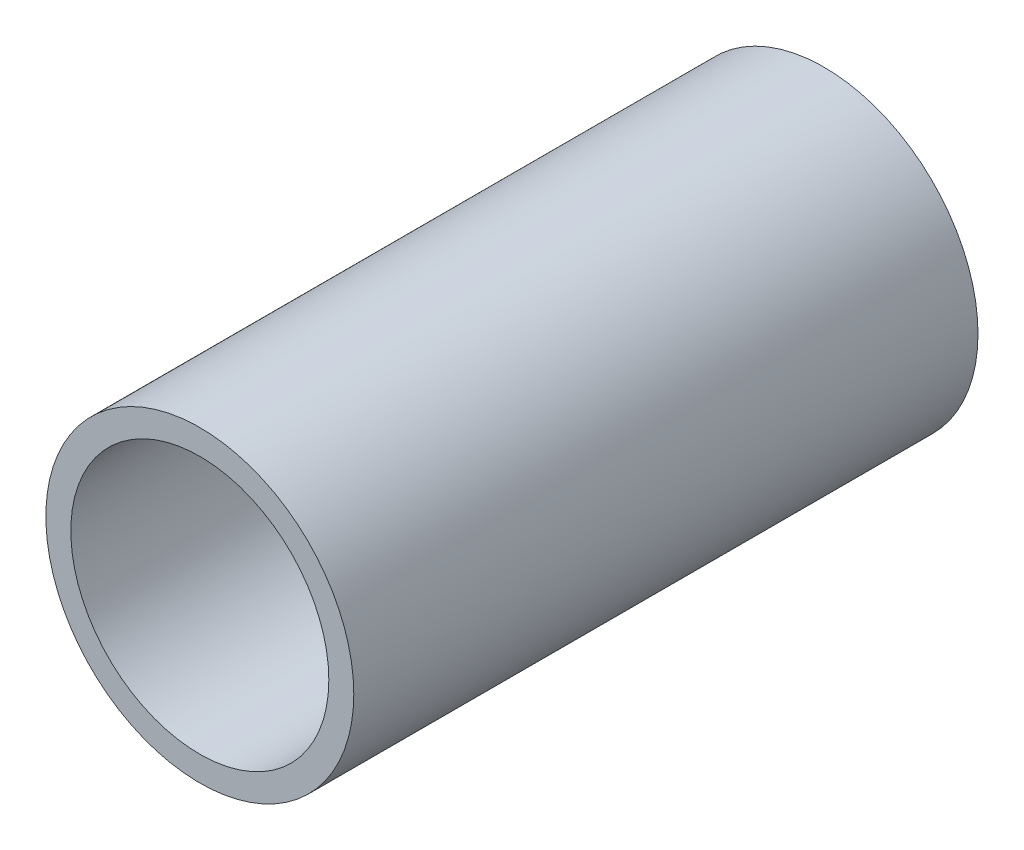
SolidWorks part; units mm, degrees
ref_plane "Front Plane" through (0, 0, 0) normal (0, 0, 1) x (1, 0, 0)
ref_plane "Top Plane" through (0, 0, 0) normal (0, 1, 0) x (1, 0, 0)
ref_plane "Right Plane" through (0, 0, 0) normal (1, 0, 0) x (0, 0, -1)
sketch "Sketch1" plane through (0, 0, 0) normal (0, 0, 1) x (1, 0, 0)
  circle A0 centre (0, 0) radius 3.1
  circle A1 centre (0, 0) radius 3.7
  dimension "D1" = 7.4
  dimension "D2" = 6.2
extrude "Boss-Extrude1" add sketch "Sketch1" along normal blind 15
